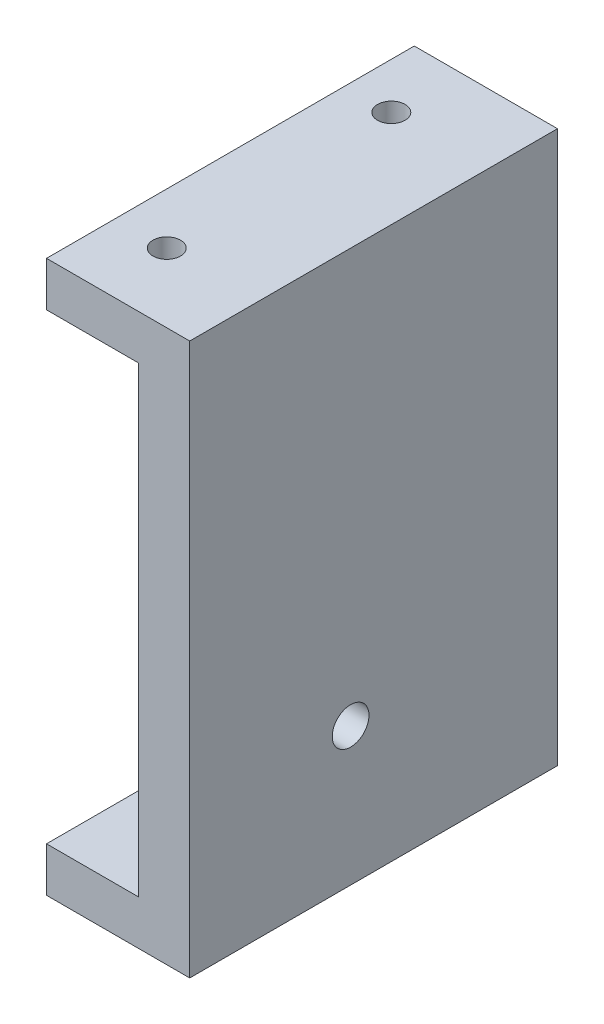
SolidWorks part; units mm, degrees
ref_plane "Front Plane" through (0, 0, 0) normal (0, 0, 1) x (1, 0, 0)
ref_plane "Top Plane" through (0, 0, 0) normal (0, 1, 0) x (1, 0, 0)
ref_plane "Right Plane" through (0, 0, 0) normal (1, 0, 0) x (0, 0, -1)
sketch "Sketch2" plane through (0, 0, 0) normal (0, 0, 1) x (1, 0, 0)
  line L0 (0, 0) -> (31.153, 0)
  line L1 (31.153, 0) -> (31.153, 120)
  line L2 (0, 110.2937) -> (0, 120)
  line L3 (20, 110.2937) -> (0, 110.2937)
  line L4 (0, 120) -> (31.153, 120)
  line L5 (20, 110.2937) -> (20, 9.7063)
  line L6 (20, 9.7063) -> (0, 9.7063)
  line L7 (0, 9.7063) -> (0, 0)
  line L8 (-25.9904, 60) -> (87.4308, 60) construction
  point P13 (20, 60)
  point P14 (31.153, 60)
  dimension "D1" = 20
  dimension "D2" = 60
extrude "Boss-Extrude1" add sketch "Sketch2" along normal blind 80
hole_wizard "Ø6.0 (6) Diameter Hole1" positions "Sketch4" profile "Sketch3" hole size "Ø6.0" standard "ANSI Metric" end condition through all
sketch "Sketch4" plane through (0, 120, 0) normal (0, 1, 0) x (1, 0, 0)
  line L0 (0, -80) -> (0, 0) construction
  line L1 (31.153, 0) -> (0, 0) construction
  point P0 (10, -15)
  dimension "D1" = 10
  dimension "D2" = 15
sketch "Sketch3" plane through (10, 120, 15) normal (1, 0, 0) x (0, 0, 1)
  line L0 (0, 0) -> (0, 120)
  line L1 (0, 120) -> (3, 120)
  line L2 (3, 120) -> (3, 0)
  line L5 (3, 0) -> (0, 0)
  line L11 (0, -6.35) -> (0, 107.95) construction
  dimension "Thru Hole Dia." = 6
  dimension "Thru Hole Depth" = 120
hole_wizard "Ø8.0 (8) Diameter Hole1" positions "Sketch6" profile "Sketch5" hole size "Ø8.0" standard "ANSI Metric" end condition through all
sketch "Sketch6" plane through (31.153, 0, 0) normal (1, 0, 0) x (0, 0, -1)
  line L0 (-80, 0) -> (0, 0) construction
  line L1 (0, 0) -> (0, 120) construction
  point P0 (-45, 30)
  dimension "D1" = 30
  dimension "D2" = 45
sketch "Sketch5" plane through (31.153, 30, 45) normal (0, 1, 0) x (0, 0, -1)
  line L0 (0, 0) -> (0, 31.153)
  line L1 (0, 31.153) -> (4, 31.153)
  line L2 (4, 31.153) -> (4, 0)
  line L5 (4, 0) -> (0, 0)
  line L11 (0, -6.35) -> (0, 107.95) construction
  dimension "Thru Hole Dia." = 8
  dimension "Thru Hole Depth" = 31.153
hole_wizard "Ø6.0 (6) Diameter Hole2" positions "Sketch8" profile "Sketch7" hole size "Ø6.0" standard "ANSI Metric" end condition through all
sketch "Sketch8" plane through (0, 120, 0) normal (0, 1, 0) x (1, 0, 0)
  line L0 (31.153, -80) -> (31.153, 0) construction
  line L1 (31.153, -80) -> (0, -80) construction
  point P0 (11.153, -65)
  dimension "D1" = 20
  dimension "D2" = 15
sketch "Sketch7" plane through (11.153, 120, 65) normal (1, 0, 0) x (0, 0, 1)
  line L0 (0, 0) -> (0, 120)
  line L1 (0, 120) -> (3, 120)
  line L2 (3, 120) -> (3, 0)
  line L5 (3, 0) -> (0, 0)
  line L11 (0, -6.35) -> (0, 107.95) construction
  dimension "Thru Hole Dia." = 6
  dimension "Thru Hole Depth" = 120
